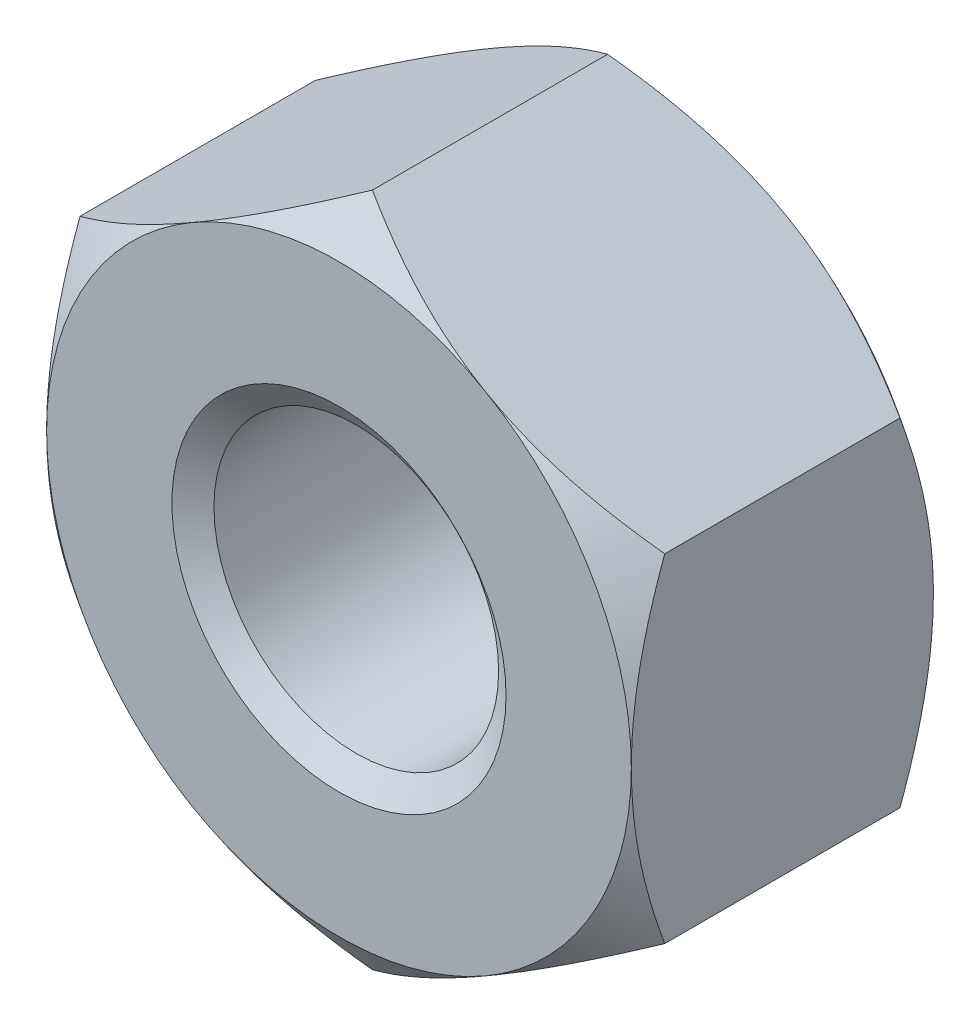
SolidWorks part; units mm, degrees
ref_plane "Plane1" through (0, 0, 0) normal (0, 0, 1) x (1, 0, 0)
ref_plane "Plane2" through (0, 0, 0) normal (0, 1, 0) x (1, 0, 0)
ref_plane "Plane3" through (0, 0, 0) normal (1, 0, 0) x (0, 0, -1)
sketch "BaseNutSke" plane through (0, 0, 0) normal (0, 0, 1) x (1, 0, 0)
  line L6 (5.5563, 3.2079) -> (5.5563, -3.2079)
  line L7 (-5.5562, 3.2079) -> (-5.5562, -3.2079)
  line L8 (5.5563, 3.2079) -> (0, 6.4158)
  line L9 (0, 6.4158) -> (-5.5562, 3.2079)
  line L10 (-5.5562, -3.2079) -> (0, -6.4158)
  line L11 (0, -6.4158) -> (5.5563, -3.2079)
  circle A0 centre (0, 0) radius 2.7051
  dimension "D4" = 5.5562
  dimension "Tap_drill" = 5.4102
  dimension "D1" = 120
  dimension "D2" = 5.5562
  dimension "D3" = 5.5562
  dimension "Width_flats" = 11.1125
extrude "BaseNut" add sketch "BaseNutSke" against normal blind 5.7404
cosmetic thread "ThreadCosmetic" [suppressed]
sketch "Sketch4" plane through (0, 0, 0) normal (1, 0, 0) x (0, 0, -1)
  line L0 (5.7404, 5.5562) -> (5.334, 5.5563)
  line L1 (5.7404, 5.5562) -> (5.7404, 19.1158)
  line L2 (5.334, 19.1158) -> (5.7404, 19.1158)
  line L3 (5.334, 19.1158) -> (5.334, 5.5563)
  line L4 (0, 0) -> (34.925, 0) construction
  line L6 (5.7404, 3.2079) -> (5.7404, 6.4158) construction
  line L7 (0, 5.5562) -> (-12.7, 5.5562)
  line L8 (0, 3.2079) -> (0, 6.4158) construction
  line L9 (0.635, 6.4158) -> (0.635, 19.1158)
  line L10 (0.635, 19.1158) -> (-12.7, 19.1158)
  line L11 (-12.7, 19.1158) -> (-12.7, 5.5562)
  line L12 (0, 5.5562) -> (0.635, 6.4158)
  line L14 (0, 3.2079) -> (0, -3.2079) construction
  line L15 (5.7404, 6.4158) -> (0, 6.4158) construction
  dimension "D1" = 5.5562
  dimension "D2" = 0.635
  dimension "Bearing_ht" = 0.4064
  dimension "D3" = 12.7
  dimension "D4" = 12.7
revolve "Bearing-Face" [suppressed] cut sketch "Sketch4" angle 360 about L4
sketch "Sketch3" plane through (0, 0, 0) normal (1, 0, 0) x (0, 0, -1)
  line L0 (5.7404, 5.5562) -> (5.1054, 6.4158)
  line L1 (5.1054, 6.4158) -> (5.1054, 19.1158)
  line L2 (5.1054, 19.1158) -> (18.4404, 19.1158)
  line L3 (18.4404, 19.1158) -> (18.4404, 5.5563)
  line L4 (18.4404, 5.5563) -> (5.7404, 5.5562)
  line L5 (5.7404, 3.2079) -> (5.7404, 6.4158) construction
  line L6 (5.7404, 6.4158) -> (0, 6.4158) construction
  line L7 (0, 0) -> (38.6776, 0) construction
  line L8 (5.7404, 0) -> (0, 0) construction
  line L9 (2.8702, 6.4158) -> (2.8702, 44.222) construction
  line L10 (0.635, 19.1158) -> (-12.7, 19.1158)
  line L11 (-12.7, 19.1158) -> (-12.7, 5.5563)
  line L12 (-12.7, 5.5563) -> (0, 5.5562)
  line L13 (0, 5.5562) -> (0.635, 6.4158)
  line L14 (0.635, 6.4158) -> (0.635, 19.1158)
  line L16 (5.7404, 6.4158) -> (0, 6.4158) construction
  dimension "D1" = 5.5562
  dimension "D2" = 0.635
  dimension "D3" = 12.7
  dimension "D4" = 12.7
revolve "Double-Chamfer" cut sketch "Sketch3" angle 360 about L7
sketch "Sketch5"
  line L0 (5.715, 3.175) -> (5.3531, 2.6581)
  line L1 (5.7658, 3.175) -> (5.715, 3.175)
  line L2 (5.7658, 3.175) -> (5.7658, 2.6581)
  line L3 (5.7658, 2.6581) -> (5.3531, 2.6581)
  line L6 (-0.0508, 3.175) -> (0, 3.175)
  line L7 (0, 3.175) -> (0.3619, 2.6581)
  line L9 (0.3619, 2.6581) -> (-0.0508, 2.6581)
  line L10 (-0.0508, 2.6581) -> (-0.0508, 3.175)
  line L11 (25.0375, 0) -> (38.388, 0) construction
  line L12 (5.7404, 0) -> (0, 0) construction
pattern_linear "ThdSchPat" [suppressed]
revolve "ThreadSchematic" cut sketch "ThdSchSke"
sketch "ThdSchSke" [suppressed] plane through (0, 0, 0) normal (0, 1, 0) x (1, 0, 0)
  line L0 (-3.175, 0.0254) -> (-2.5527, 0.4611)
  line L1 (-2.5527, 0.4611) -> (-1.2763, 0.4611)
  line L2 (-1.2763, 0.4611) -> (-1.2763, -0.4103)
  line L3 (-1.2763, -0.4103) -> (-2.5527, -0.4103)
  line L4 (-2.5527, -0.4103) -> (-3.175, 0.0254)
  line L5 (-3.175, 0.9068) -> (3.175, 0.9068) construction
  line L6 (0, 0.9068) -> (0, -2.9874) construction
  line L7 (0, 5.2793) -> (0, 0.4357) construction
  dimension "D1" = 35
  dimension "VeeAngle" = 70
  dimension "SideAngle" = 55
  dimension "D2" = 0.0508
  dimension "OverCut" = 2.7051
  dimension "Tap_Drill" = 5.4102
  dimension "Advance" = 0.8128
  dimension "Thread_major" = 6.35
  dimension "Num_threads" = 8
  dimension "D4" = 50
  dimension "Offset1" = 5.7658
  dimension "ThreadMajor" = 3.175
  dimension "ChamferDepth" = 0.5169
  dimension "Offset2" = 5.8166
revolve "EndChamfer" cut sketch "Sketch5" angle 360 about L11
equation "\"D2@BaseNutSke\" = \"Width_flats@BaseNutSke\" / 2"
equation "\"D3@BaseNutSke\" = \"Width_flats@BaseNutSke\" / 2"
equation "\"D1@Sketch3\" = \"Width_flats@BaseNutSke\" /2"
equation "\"D2@Sketch3\" = \"Thread_major@ThreadCosmetic\" *.1"
equation "\"D1@Sketch4\" = \"D2@BaseNutSke\""
equation "\"D2@Sketch4\" = \"Thread_major@ThreadCosmetic\" *.10"
equation "\"D4@BaseNutSke\" = \"D3@BaseNutSke\""
equation "\"Thread_major@ThdSchSke\" = \"Thread_major@ThreadCosmetic\""
equation "\"Tap_drill@ThdSchSke\" = \"Tap_drill@BaseNutSke\""
equation "\"Overcut@ThdSchSke\" = \"Tap_drill@ThdSchSke\" * 0.5"
equation "\"Num_threads@ThdSchPat\" = int(  ( \"Thickness@BaseNut\" - 0.002 ) / \"Advance@ThdSchSke\" + 0.999 )  + 1"
equation "\"Advance@ThdSchPat\" = ( \"Thickness@BaseNut\" - 0.002 ) /  (\"Num_threads@ThdSchPat\" - 1) 'relax it"
equation "' \"Num_threads@ThdSchPat\" = \"Num_threads@ThdSchPat\" - sgn( \"Num_threads@ThdSchPat\" - 1) '---chamfered tips only---"
equation "\"ThreadMajor@Sketch5\" = \"Thread_major@ThreadCosmetic\" * 0.5"
equation "\"ChamferDepth@Sketch5\" = (\"Thread_major@ThreadCosmetic\" - \"Tap_drill@BaseNutSke\") * 0.55"
equation "\"Offset1@Sketch5\" = \"Thickness@BaseNut\" + 0.001"
equation "\"Offset2@Sketch5\" = \"Offset1@Sketch5\" + 0.002"
